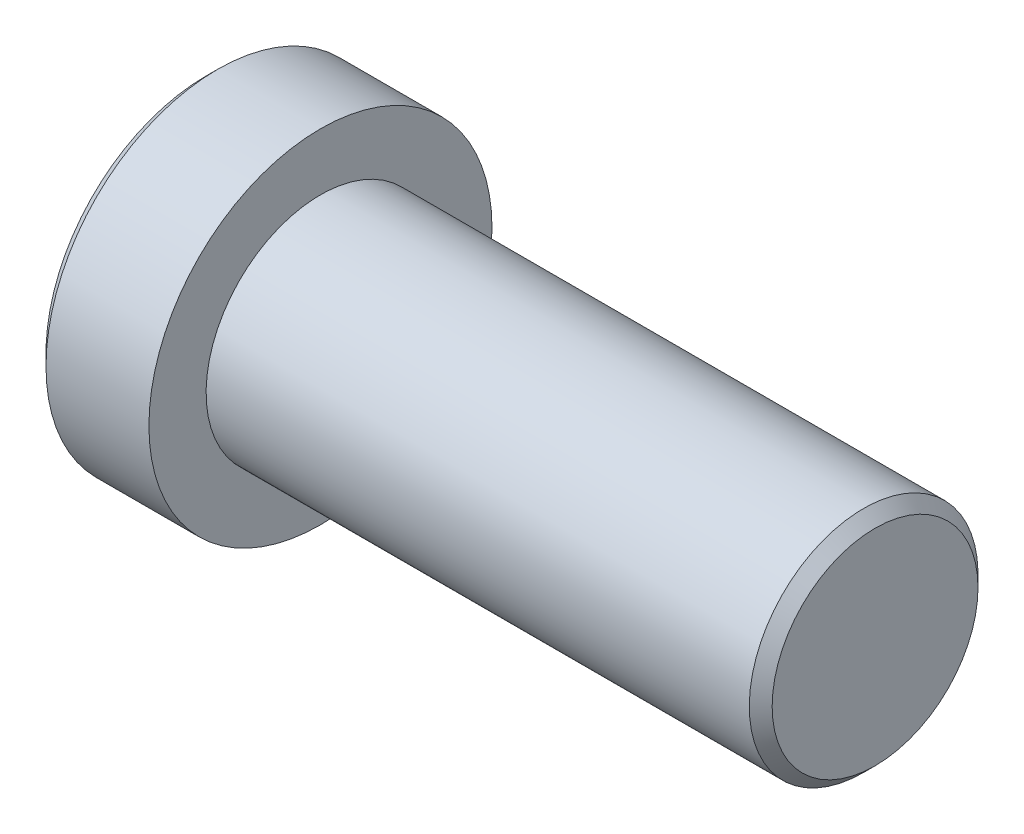
SolidWorks part; units mm, degrees
material "AISI 4130 Steel, normalized at 870C"
ref_plane "Front Plane" through (0, 0, 0) normal (0, 0, 1) x (1, 0, 0)
ref_plane "Top Plane" through (0, 0, 0) normal (0, 1, 0) x (1, 0, 0)
ref_plane "Right Plane" through (0, 0, 0) normal (1, 0, 0) x (0, 0, -1)
sketch "Sketch1" plane through (0, 0, 0) normal (0, 0, 1) x (1, 0, 0)
  line L0 (0, 0) -> (0, 3)
  line L1 (0, 3) -> (2, 3)
  line L2 (2, 3) -> (2, 2)
  line L3 (2, 2) -> (11.7, 2)
  line L4 (11.7, 2) -> (11.7, 0)
  line L5 (11.7, 0) -> (0, 0)
  line L6 (0, 0) -> (11.8242, 0) construction
  dimension "D1" = 9.7
  dimension "D2" = 2
  dimension "D3" = 2
  dimension "D4" = 3
revolve "Revolve1" add sketch "Sketch1" angle 360 about L6
cosmetic thread "Cosmetic Thread1" parameters "D1"=4, "D2"=3.22
sketch "Sketch2" plane through (0, 0, 0) normal (-1, 0, 0) x (0, 0, 1)
  line L0 (0, 0) -> (0, 2) construction
  line L1 (0, 2) -> (-1.7321, 1)
  line L2 (-1.7321, 1) -> (-1.7321, -1)
  line L3 (-1.7321, -1) -> (0, -2)
  line L4 (0, -2) -> (1.7321, -1)
  line L5 (1.7321, -1) -> (1.7321, 1)
  line L6 (1.7321, 1) -> (0, 2)
  line L7 (0, 0) -> (1.7321, 1) construction
  circle A0 centre (0, 0) radius 1.7321 construction
  dimension "D1" = 2
extrude "Cut-Extrude1" cut sketch "Sketch2" against normal blind 1.5
chamfer "Chamfer1" distance 0.2 angle 45 2 edges at (0, -3, 0) (11.7, -2, 0)
